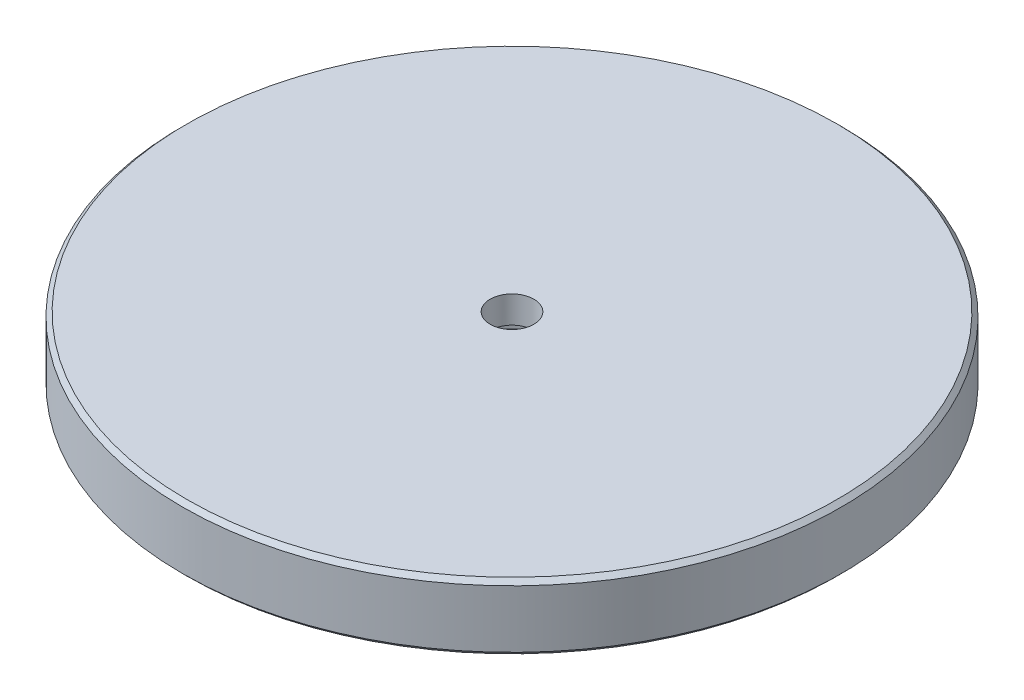
SolidWorks part; units mm, degrees
material "Glass"
ref_plane "Front Plane" through (0, 0, 0) normal (0, 0, 1) x (1, 0, 0)
ref_plane "Top Plane" through (0, 0, 0) normal (0, 1, 0) x (1, 0, 0)
ref_plane "Right Plane" through (0, 0, 0) normal (1, 0, 0) x (0, 0, -1)
sketch "Sketch1" plane through (0, 0, 0) normal (0, 1, 0) x (1, 0, 0)
  circle A0 centre (0, 0) radius 75.5
  dimension "D1" = 151
extrude "Boss-Extrude1" add sketch "Sketch1" along normal blind 15.2
sketch "Sketch2" plane through (0, 0, 0) normal (0, -1, 0) x (1, 0, 0)
  circle A0 centre (0, 0) radius 15.2
  dimension "D1" = 30.4
extrude "Cut-Extrude1" cut sketch "Sketch2" against normal blind 9
chamfer "Chamfer1" distance 1 angle 45 1 edges at (0, 0, -15.2)
sketch "Sketch4" plane through (0, 9, 0) normal (0, -1, 0) x (1, 0, 0)
  circle A0 centre (0, 0) radius 5
  dimension "D1" = 10
extrude "Cut-Extrude2" cut sketch "Sketch4" against normal blind 28
chamfer "Chamfer2" distance 1 angle 45 2 edges at (0, 15.2, 75.5) (0, 0, 75.5)
